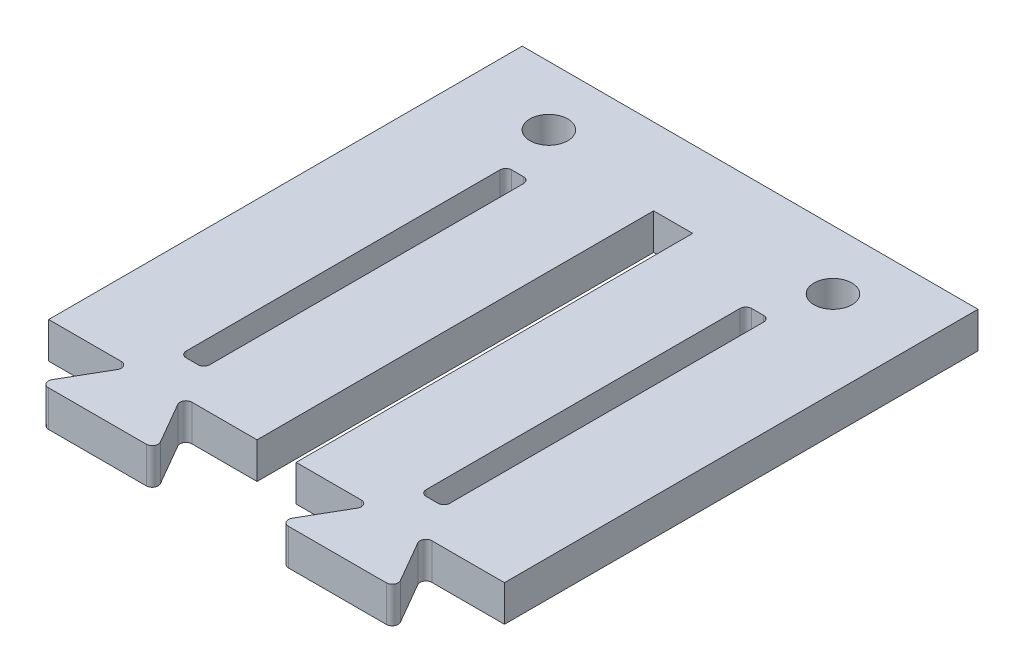
SolidWorks part; units mm, degrees
ref_plane "Front Plane" through (0, 0, 0) normal (0, 0, 1) x (1, 0, 0)
ref_plane "Top Plane" through (0, 0, 0) normal (0, 1, 0) x (1, 0, 0)
ref_plane "Right Plane" through (0, 0, 0) normal (1, 0, 0) x (0, 0, -1)
sketch "Sketch1" plane through (0, 0, 0) normal (0, 1, 0) x (1, 0, 0)
  line L0 (-19.25, 0) -> (-19.25, 40)
  line L1 (-19.25, 40) -> (19.25, 40)
  line L2 (19.25, 40) -> (19.25, 0)
  line L3 (19.25, 0) -> (12.25, 0)
  line L4 (12.25, 0) -> (15.1368, -5)
  line L5 (15.1368, -5) -> (5.1368, -5)
  line L6 (5.1368, -5) -> (8.0235, 0)
  line L7 (8.0235, 0) -> (-8.0235, 0)
  line L8 (-8.0235, 0) -> (-5.1368, -5)
  line L9 (-5.1368, -5) -> (-15.1368, -5)
  line L10 (-15.1368, -5) -> (-12.25, 0)
  line L11 (-12.25, 0) -> (-19.25, 0)
  point P13 (0, 0)
  dimension "D1" = 40
  dimension "D2" = 38.5
  dimension "D3" = 10
  dimension "D4" = 10
  dimension "D5" = 60
  dimension "D6" = 60
  dimension "D7" = 7
  dimension "D8" = 7
  dimension "D9" = 5
  dimension "D10" = 5
extrude "Boss-Extrude1" add sketch "Sketch1" along normal blind 3.05
fillet "Fillet1" radius 0.5 8 edges at (12.25, 1.525, 0) (15.1368, 1.525, 5) (5.1368, 1.525, 5) (8.0235, 1.525, 0) (-8.0235, 1.525, 0) (-5.1368, 1.525, 5) (-15.1368, 1.525, 5) (-12.25, 1.525, 0)
sketch "Sketch3" plane through (0, 3.05, 0) normal (0, 1, 0) x (1, 0, 0)
  line L0 (0, 40) -> (0, 0) construction
  line L2 (19.25, 40) -> (-19.25, 40) construction
  line L3 (-1.65, 33.5) -> (1.65, 33.5)
  line L4 (-1.65, 33.5) -> (-1.65, -28.3)
  line L5 (-1.65, -28.3) -> (1.65, -28.3)
  line L6 (1.65, 33.5) -> (1.65, -28.3)
  line L8 (-1.65, -29.5) -> (1.65, -29.5)
  line L9 (-1.65, -29.5) -> (-1.65, -30.5)
  line L10 (-1.65, -30.5) -> (1.65, -30.5)
  line L11 (1.65, -29.5) -> (1.65, -30.5)
  point P8 (0, 33.5)
  point P15 (0, -29.5)
  dimension "D1" = 3.3
  dimension "D2" = 61.8
  dimension "D3" = 6.5
  dimension "D4" = 1.2
  dimension "D5" = 1
extrude "Cut-Extrude2" cut sketch "Sketch3" against normal through all
sketch "Sketch8" plane through (0, 3.05, 0) normal (0, 1, 0) x (1, 0, 0)
  line L0 (0, 0) -> (0, 40) construction
  line L1 (-11.1368, 30.5) -> (-9.1368, 30.5)
  line L2 (-11.1368, 30.5) -> (-11.1368, 3)
  line L3 (-11.1368, 3) -> (-9.1368, 3)
  line L4 (-9.1368, 30.5) -> (-9.1368, 3)
  line L5 (-19.25, 0) -> (-13.116, 0) construction
  line L6 (-14.2707, -5) -> (-6.0028, -5) construction
  line L8 (11.1368, 3) -> (9.1368, 3)
  line L9 (9.1368, 30.5) -> (9.1368, 3)
  line L10 (11.1368, 30.5) -> (9.1368, 30.5)
  line L11 (11.1368, 30.5) -> (11.1368, 3)
  line L12 (1.65, 33.5) -> (-1.65, 33.5) construction
  point P5 (-10.1368, -5)
  point P10 (-10.1368, 3)
  dimension "D1" = 2
  dimension "D2" = 3
  dimension "D3" = 3
extrude "Cut-Extrude3" cut sketch "Sketch8" against normal through all
fillet "Fillet2" radius 0.5 8 edges at (11.1368, 1.525, -3) (9.1368, 1.525, -3) (11.1368, 1.525, -30.5) (9.1368, 1.525, -30.5) (-9.1368, 1.525, -3) (-9.1368, 1.525, -30.5) (-11.1368, 1.525, -30.5) (-11.1368, 1.525, -3)
sketch "Damper Hole Locations" plane through (0, 3.05, 0) normal (0, 1, 0) x (1, 0, 0)
  line L0 (0, 40) -> (0, 0) construction
  line L3 (19.25, 40) -> (-19.25, 40) construction
  circle A0 centre (-12, 35) radius 1.5
  circle A1 centre (12, 35) radius 1.5
  dimension "D1" = 3
  dimension "D2" = 12
  dimension "D3" = 5
hole_wizard "M3 Clearance Damper Holes" positions "Sketch6" profile "Sketch7" hole size "M3" standard "ANSI Metric" end condition through all
sketch "Sketch6" plane through (0, 3.05, 0) normal (0, 1, 0) x (1, 0, 0)
  point P0 (-12, 35)
  point P3 (12, 35)
sketch "Sketch7" plane through (-12, 3.05, -35) normal (1, 0, 0) x (0, 0, 1)
  line L0 (0, 0) -> (0, 3.05)
  line L1 (0, 3.05) -> (1.6, 3.05)
  line L2 (1.6, 3.05) -> (1.6, 0)
  line L5 (1.6, 0) -> (0, 0)
  line L11 (0, -6.35) -> (0, 107.95) construction
  dimension "Thru Hole Dia." = 3.2
  dimension "Thru Hole Depth" = 3.05
